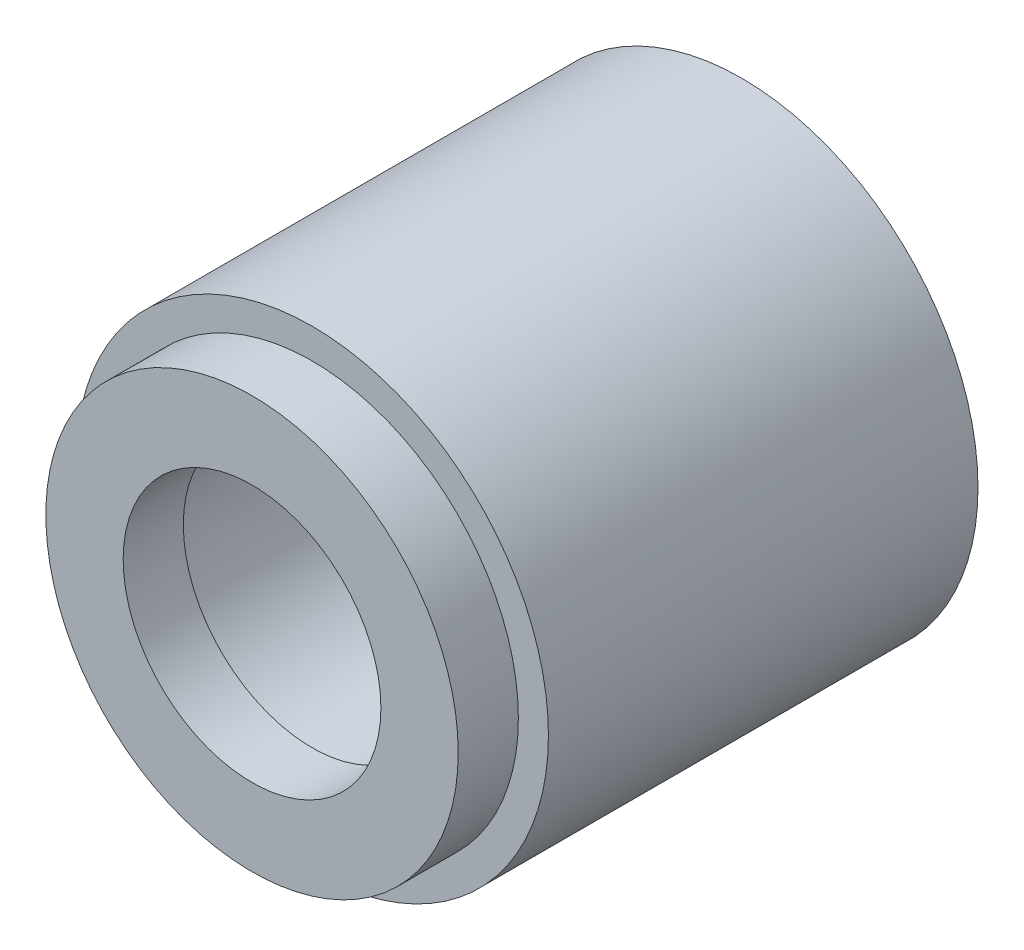
SolidWorks part; units mm, degrees
ref_plane "Front Plane" through (0, 0, 0) normal (0, 0, 1) x (1, 0, 0)
ref_plane "Top Plane" through (0, 0, 0) normal (0, 1, 0) x (1, 0, 0)
ref_plane "Right Plane" through (0, 0, 0) normal (1, 0, 0) x (0, 0, -1)
sketch "Sketch1" plane through (0, 0, 0) normal (0, 0, 1) x (1, 0, 0)
  circle A0 centre (0, 0) radius 2.75
  circle A1 centre (0, 0) radius 1.6
  dimension "D1" = 3.2
  dimension "D2" = 5.5
extrude "Boss-Extrude1" add sketch "Sketch1" along normal blind 5
sketch "Sketch2" plane through (0, 0, 5) normal (0, 0, 1) x (1, 0, 0)
  circle A0 centre (0, 0) radius 1.5
  circle A1 centre (0, 0) radius 2.4
  dimension "D1" = 4.8
extrude "Boss-Extrude2" add sketch "Sketch2" along normal blind 0.7
